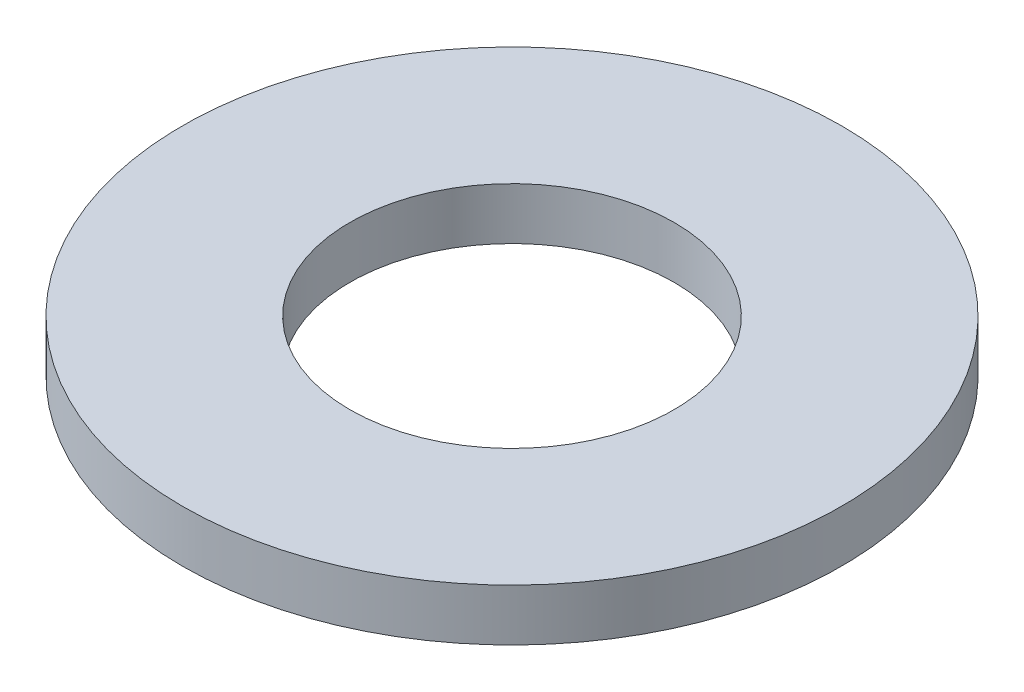
SolidWorks part; units mm, degrees
material "Baltic Birch"
ref_plane "Front Plane" through (0, 0, 0) normal (0, 0, 1) x (1, 0, 0)
ref_plane "Top Plane" through (0, 0, 0) normal (0, 1, 0) x (1, 0, 0)
ref_plane "Right Plane" through (0, 0, 0) normal (1, 0, 0) x (0, 0, -1)
sketch "Sketch2" plane through (0, 0, 0) normal (0, 1, 0) x (1, 0, 0)
  circle A0 centre (0, 0) radius 76.2
  dimension "D1" = 152.4
extrude "Boss-Extrude1" add sketch "Sketch2" along normal blind 12
sketch "Sketch3" plane through (0, 12, 0) normal (0, 1, 0) x (1, 0, 0)
  circle A0 centre (0, 0) radius 37.5
  dimension "D1" = 75
extrude "Cut-Extrude1" cut sketch "Sketch3" against normal through all
